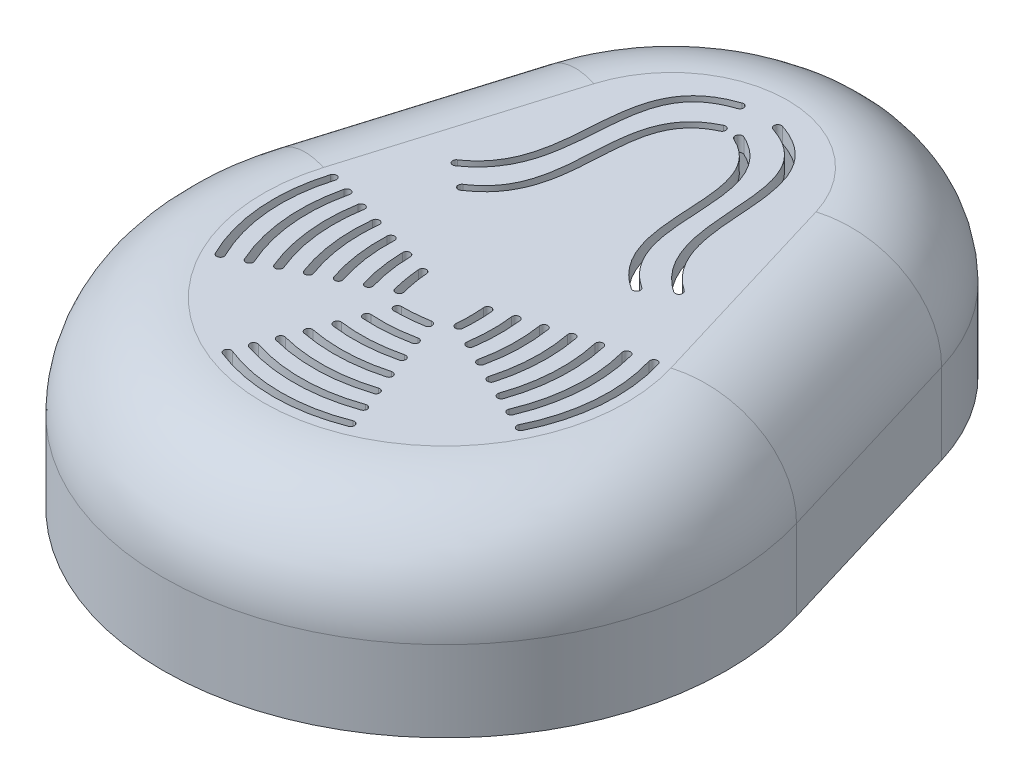
SolidWorks part; units mm, degrees
ref_plane "Alzado" through (0, 0, 0) normal (0, 0, 1) x (1, 0, 0)
ref_plane "Planta" through (0, 0, 0) normal (0, 1, 0) x (1, 0, 0)
ref_plane "Vista lateral" through (0, 0, 0) normal (1, 0, 0) x (0, 0, -1)
sketch "Croquis6" plane through (0, 0, 0) normal (0, 1, 0) x (1, 0, 0)
  line L0 (-53.6123, 2.1778) -> (-41.1666, 43.4222)
  line L1 (41.1666, 43.4222) -> (53.6123, 2.1778)
  arc A0 (41.1666, 43.4222) -> (-41.1666, 43.4222) centre (0, 31) ccw
  arc A1 (-53.6123, 2.1778) -> (53.6123, 2.1778) centre (0, -14) ccw
  dimension "D2" = 43
  dimension "D3" = 56
  dimension "D1" = 45
  dimension "D4" = 14
extrude "Saliente-Extruir3" add sketch "Croquis6" along normal blind 36
fillet "Redondeo1" radius 20 4 edges at (0, 36, -74) (-47.3895, 36, -22.8) (0, 36, 70) (47.3895, 36, -22.8)
shell "Vaciado1" thickness 3
sketch "Croquis8" plane through (0, 36, 0) normal (0, 1, 0) x (1, 0, 0)
  line L0 (-7.4874, -11.7407) -> (-32.5503, -4.1778) construction
  line L1 (-30.4675, -29.0909) -> (-6.5155, -17.4301) construction
  line L2 (-33.8818, -16.8327) -> (0, -14) construction
  line L3 (-7.4874, -11.7407) -> (-6.5155, -17.4301) construction
  line L4 (0, -14) -> (0, 54) construction
  line L5 (-22.5, 11) -> (-17.7432, 7.3431) construction
  line L6 (-32.0937, -23.6844) -> (-6.5898, -15.9885) construction
  line L7 (-16, 21) -> (-11.2432, 17.3431) construction
  line L8 (-53.6123, 2.1778) -> (-34.4651, -3.6) construction
  line L9 (53.6123, 2.1778) -> (34.4651, -3.6) construction
  line L10 (-2.8753, -21.2731) -> (-12.5, -45.6188) construction
  line L11 (12.5, -45.6188) -> (2.8753, -20.7786) construction
  line L12 (-2.8753, -21.2731) -> (2.8753, -20.7786) construction
  line L13 (7.0082, -17.4713) -> (30.4675, -29.0909) construction
  line L14 (32.5503, -4.1778) -> (6.9946, -11.6995) construction
  line L15 (7.0082, -17.4713) -> (6.9946, -11.6995) construction
  line L16 (-6.6429, -10.2169) -> (-30.1809, 1.2423) construction
  line L17 (36.2644, -6.0707) -> (11.4572, -15.7801) construction
  line L18 (11.9713, -21.529) -> (36.3497, -31.0705) construction
  line L19 (-8.2432, 37.3431) -> (-13, 41) construction
  line L20 (-4, 49) -> (-2, 43.3431) construction
  arc A0 (-32.5503, -4.1778) -> (-30.4675, -29.0909) centre (0, -14) ccw
  arc A1 (-34.4651, -3.6) -> (34.4651, -3.6) centre (0, -14) ccw construction
  arc A2 (-28.6933, -5.3417) -> (-26.5651, -27.1911) centre (4.3987, -13.1468) ccw
  arc A3 (-24.7127, -6.5428) -> (-22.6273, -25.274) centre (8.7974, -12.2936) ccw
  arc A4 (-20.6065, -7.7819) -> (-18.6538, -23.3395) centre (13.1961, -11.4405) ccw
  arc A5 (-16.3709, -9.06) -> (-14.6443, -21.3875) centre (17.5948, -10.5873) ccw
  arc A6 (-12.0004, -10.3788) -> (-10.5983, -19.4178) centre (21.9935, -9.7341) ccw
  arc A7 (-7.4874, -11.7407) -> (-6.5155, -17.4301) centre (26.3922, -8.8809) ccw
  arc A8 (-31.1143, -4.6111) -> (-29.1233, -28.4251) centre (0, -14) ccw
  arc A9 (-27.2333, -5.686) -> (-25.1991, -26.5715) centre (4.3987, -13.1468) ccw
  arc A10 (-23.2343, -6.7965) -> (-21.2409, -24.7013) centre (8.7974, -12.2936) ccw
  arc A11 (-19.1152, -7.9433) -> (-17.2486, -22.8145) centre (13.1961, -11.4405) ccw
  arc A12 (-14.8724, -9.1274) -> (-13.2219, -20.911) centre (17.5948, -10.5873) ccw
  arc A13 (-10.5007, -10.3504) -> (-9.1605, -18.9905) centre (21.9935, -9.7341) ccw
  arc A14 (-5.9927, -11.6145) -> (-5.0637, -17.0529) centre (26.3922, -8.8809) ccw
  arc A15 (-32.5503, -4.1778) -> (-31.1143, -4.6111) centre (-31.8323, -4.3944) cw
  arc A16 (-30.4675, -29.0909) -> (-29.1233, -28.4251) centre (-29.7954, -28.758) ccw
  arc A17 (-28.6933, -5.3417) -> (-27.2333, -5.686) centre (-27.9633, -5.5138) cw
  arc A18 (-26.5651, -27.1911) -> (-25.1991, -26.5715) centre (-25.8821, -26.8813) ccw
  arc A19 (-24.7127, -6.5428) -> (-23.2343, -6.7965) centre (-23.9735, -6.6697) cw
  arc A20 (-22.6273, -25.274) -> (-21.2409, -24.7013) centre (-21.9341, -24.9876) ccw
  arc A21 (-20.6065, -7.7819) -> (-19.1152, -7.9433) centre (-19.8609, -7.8626) cw
  arc A22 (-18.6538, -23.3395) -> (-17.2486, -22.8145) centre (-17.9512, -23.077) ccw
  arc A23 (-16.3709, -9.06) -> (-14.8724, -9.1274) centre (-15.6217, -9.0937) cw
  arc A24 (-14.6443, -21.3875) -> (-13.2219, -20.911) centre (-13.9331, -21.1492) ccw
  arc A25 (-12.0004, -10.3788) -> (-10.5007, -10.3504) centre (-11.2505, -10.3646) cw
  arc A26 (-10.5983, -19.4178) -> (-9.1605, -18.9905) centre (-9.8794, -19.2042) ccw
  arc A27 (-7.4874, -11.7407) -> (-5.9927, -11.6145) centre (-6.74, -11.6776) cw
  arc A28 (-6.5155, -17.4301) -> (-5.0637, -17.0529) centre (-5.7896, -17.2415) ccw
  arc A29 (-12.5, -45.6188) -> (12.5, -45.6188) centre (0, -14) ccw
  arc A30 (-11.0188, -41.8722) -> (10.9319, -41.5718) centre (-0.4837, -9.5455) ccw
  arc A31 (-9.4902, -38.0055) -> (9.3496, -37.4879) centre (-0.9675, -5.091) ccw
  arc A32 (-7.9133, -34.0168) -> (7.7529, -33.367) centre (-1.4512, -0.6365) ccw
  arc A33 (-6.2868, -29.9024) -> (6.1417, -29.2088) centre (-1.935, 3.8179) ccw
  arc A34 (-4.6084, -25.657) -> (4.5159, -25.0129) centre (-2.4187, 8.2724) ccw
  arc A35 (-2.8753, -21.2731) -> (2.8753, -20.7786) centre (-2.9024, 12.7269) ccw
  arc A36 (-11.9485, -44.2239) -> (11.9485, -44.2239) centre (0, -14) ccw
  arc A37 (-10.554, -40.446) -> (10.4283, -40.1589) centre (-0.4837, -9.5455) ccw
  arc A38 (-9.1142, -36.5534) -> (8.8944, -36.0586) centre (-0.9675, -5.091) ccw
  arc A39 (-7.6282, -32.5441) -> (7.3468, -31.923) centre (-1.4512, -0.6365) ccw
  arc A40 (-6.0948, -28.4147) -> (5.7854, -27.7518) centre (-1.935, 3.8179) ccw
  arc A41 (-4.5118, -24.1601) -> (4.21, -23.5444) centre (-2.4187, 8.2724) ccw
  arc A42 (-2.8765, -19.7731) -> (2.6204, -19.3004) centre (-2.9024, 12.7269) ccw
  arc A43 (-12.5, -45.6188) -> (-11.9485, -44.2239) centre (-12.2243, -44.9213) cw
  arc A44 (12.5, -45.6188) -> (11.9485, -44.2239) centre (12.2243, -44.9213) ccw
  arc A45 (-11.0188, -41.8722) -> (-10.554, -40.446) centre (-10.7864, -41.1591) cw
  arc A46 (10.9319, -41.5718) -> (10.4283, -40.1589) centre (10.6801, -40.8653) ccw
  arc A47 (-9.4902, -38.0055) -> (-9.1142, -36.5534) centre (-9.3022, -37.2795) cw
  arc A48 (9.3496, -37.4879) -> (8.8944, -36.0586) centre (9.122, -36.7733) ccw
  arc A49 (-7.9133, -34.0168) -> (-7.6282, -32.5441) centre (-7.7708, -33.2805) cw
  arc A50 (7.7529, -33.367) -> (7.3468, -31.923) centre (7.5498, -32.645) ccw
  arc A51 (-6.2868, -29.9024) -> (-6.0948, -28.4147) centre (-6.1908, -29.1586) cw
  arc A52 (6.1417, -29.2088) -> (5.7854, -27.7518) centre (5.9636, -28.4803) ccw
  arc A53 (-4.6084, -25.657) -> (-4.5118, -24.1601) centre (-4.5601, -24.9085) cw
  arc A54 (4.5159, -25.0129) -> (4.21, -23.5444) centre (4.363, -24.2786) ccw
  arc A55 (-2.8753, -21.2731) -> (-2.8765, -19.7731) centre (-2.8759, -20.5231) cw
  arc A56 (2.8753, -20.7786) -> (2.6204, -19.3004) centre (2.7478, -20.0395) ccw
  arc A57 (30.4675, -29.0909) -> (32.5503, -4.1778) centre (0, -14) ccw
  arc A58 (26.8572, -27.3027) -> (28.3867, -5.4032) centre (-4.4793, -14.1109) ccw
  arc A59 (23.1314, -25.4572) -> (24.1852, -6.6398) centre (-8.9586, -14.2219) ccw
  arc A60 (19.2879, -23.5535) -> (19.9456, -7.8876) centre (-13.4379, -14.3328) ccw
  arc A61 (15.3233, -21.5898) -> (15.6676, -9.1468) centre (-17.9172, -14.4437) ccw
  arc A62 (11.2325, -19.5636) -> (11.3508, -10.4173) centre (-22.3965, -14.5547) ccw
  arc A63 (7.0082, -17.4713) -> (6.9946, -11.6995) centre (-26.8758, -14.6656) ccw
  arc A64 (29.1233, -28.4251) -> (31.1143, -4.6111) centre (0, -14) ccw
  arc A65 (25.4747, -26.7207) -> (26.9368, -5.7874) centre (-4.4793, -14.1109) ccw
  arc A66 (21.7156, -24.9615) -> (22.723, -6.9743) centre (-8.9586, -14.2219) ccw
  arc A67 (17.8441, -23.1467) -> (18.4728, -8.172) centre (-13.4379, -14.3328) ccw
  arc A68 (13.8568, -21.2745) -> (14.186, -9.3804) centre (-17.9172, -14.4437) ccw
  arc A69 (9.7489, -19.3426) -> (9.862, -10.5998) centre (-22.3965, -14.5547) ccw
  arc A70 (5.5134, -17.3475) -> (5.5003, -11.8303) centre (-26.8758, -14.6656) ccw
  arc A71 (30.4675, -29.0909) -> (29.1233, -28.4251) centre (29.7954, -28.758) cw
  arc A72 (32.5503, -4.1778) -> (31.1143, -4.6111) centre (31.8323, -4.3944) ccw
  arc A73 (26.8572, -27.3027) -> (25.4747, -26.7207) centre (26.166, -27.0117) cw
  arc A74 (28.3867, -5.4032) -> (26.9368, -5.7874) centre (27.6617, -5.5953) ccw
  arc A75 (23.1314, -25.4572) -> (21.7156, -24.9615) centre (22.4235, -25.2094) cw
  arc A76 (24.1852, -6.6398) -> (22.723, -6.9743) centre (23.4541, -6.8071) ccw
  arc A77 (19.2879, -23.5535) -> (17.8441, -23.1467) centre (18.566, -23.3501) cw
  arc A78 (19.9456, -7.8876) -> (18.4728, -8.172) centre (19.2092, -8.0298) ccw
  arc A79 (15.3233, -21.5898) -> (13.8568, -21.2745) centre (14.5901, -21.4322) cw
  arc A80 (15.6676, -9.1468) -> (14.186, -9.3804) centre (14.9268, -9.2636) ccw
  arc A81 (11.2325, -19.5636) -> (9.7489, -19.3426) centre (10.4907, -19.4531) cw
  arc A82 (11.3508, -10.4173) -> (9.862, -10.5998) centre (10.6064, -10.5086) ccw
  arc A83 (7.0082, -17.4713) -> (5.5134, -17.3475) centre (6.2608, -17.4094) cw
  arc A84 (6.9946, -11.6995) -> (5.5003, -11.8303) centre (6.2474, -11.7649) ccw
  arc A85 (22.0193, 37.6444) -> (-22.0193, 37.6444) centre (0, 31) ccw construction
  arc A86 (-4, 49) -> (-3.5263, 47.5768) centre (-3.7631, 48.2884) cw
  arc A87 (-22.5, 11) -> (-21.655, 9.7606) centre (-22.0775, 10.3803) ccw
  arc A88 (-2, 43.3431) -> (-1.3615, 41.9858) centre (-1.6807, 42.6645) cw
  arc A89 (-17.7432, 7.3431) -> (-16.9293, 6.0832) centre (-17.3362, 6.7132) ccw
  arc A90 (4, 49) -> (3.5263, 47.5768) centre (3.7631, 48.2884) ccw
  arc A91 (22.5, 11) -> (21.655, 9.7606) centre (22.0775, 10.3803) cw
  arc A92 (2, 43.3431) -> (1.3615, 41.9858) centre (1.6807, 42.6645) ccw
  arc A93 (17.7432, 7.3431) -> (16.9293, 6.0832) centre (17.3362, 6.7132) cw
  spline S0 degree 3 poles (-4, 49) (-22.3057, 42.9068) (-8.3543, 20.6444) (-22.5, 11) knots 0 0 0 0 1 1 1 1
  spline S1 degree 3 poles (-2, 43.3431) (-16.8249, 36.3689) (-4.2167, 16.0809) (-17.7432, 7.3431) knots 0 0 0 0 1 1 1 1
  spline S2 degree 3 poles (4, 49) (22.3057, 42.9068) (8.3543, 20.6444) (22.5, 11) knots 0 0 0 0 1 1 1 1
  spline S3 degree 3 poles (2, 43.3431) (16.8249, 36.3689) (4.2167, 16.0809) (17.7432, 7.3431) knots 0 0 0 0 1 1 1 1
  spline S4 degree 1 poles (-3.5263, 47.5768) (-21.655, 9.7606) knots 0 0 1 1 construction
  spline S5 degree 3 poles (-3.5263, 47.5768) (-3.7864, 47.4902) (-4.3118, 47.3031) (-5.2759, 46.9108) (-6.3734, 46.3724) (-7.5179, 45.6615) (-8.842, 44.6317) (-10.1604, 43.1989) (-11.3276, 41.2396) (-12.1619, 39.0334) (-12.9152, 35.7913) (-13.3453, 31.2785) (-13.6752, 25.5051) (-14.3981, 20.6711) (-15.6553, 16.9525) (-17.0463, 14.2974) (-18.6669, 12.2566) (-20.2605, 10.7791) (-21.1848, 10.0812) (-21.655, 9.7606) knots 0 0 0 0 0.015625 0.03125 0.0625 0.09375 0.125 0.1875 0.25 0.3125 0.375 0.5 0.625 0.75 0.8125 0.875 0.9375 0.96875 1 1 1 1
  spline S6 degree 1 poles (-1.3615, 41.9858) (-16.9293, 6.0832) knots 0 0 1 1 construction
  spline S7 degree 3 poles (-1.3615, 41.9858) (-1.766, 41.7955) (-2.5811, 41.3654) (-3.9442, 40.4606) (-5.3288, 39.1895) (-6.556, 37.465) (-7.4507, 35.521) (-8.0696, 33.3632) (-8.6022, 30.2377) (-8.8703, 25.9645) (-9.1351, 20.576) (-9.8541, 16.0966) (-11.1027, 12.6635) (-12.4731, 10.2215) (-14.0519, 8.3546) (-15.5905, 7.0087) (-16.4788, 6.3741) (-16.9293, 6.0832) knots 0 0 0 0 0.03125 0.0625 0.125 0.1875 0.25 0.3125 0.375 0.5 0.625 0.75 0.8125 0.875 0.9375 0.96875 1 1 1 1
  spline S8 degree 1 poles (3.5263, 47.5768) (21.655, 9.7606) knots 0 0 1 1 construction
  spline S9 degree 3 poles (3.5263, 47.5768) (3.7864, 47.4902) (4.3118, 47.3031) (5.2759, 46.9108) (6.3734, 46.3724) (7.5179, 45.6615) (8.842, 44.6317) (10.1604, 43.1989) (11.3276, 41.2396) (12.1619, 39.0334) (12.9152, 35.7913) (13.3453, 31.2785) (13.6752, 25.5051) (14.3981, 20.6711) (15.6553, 16.9525) (17.0463, 14.2974) (18.6669, 12.2566) (20.2605, 10.7791) (21.1848, 10.0812) (21.655, 9.7606) knots 0 0 0 0 0.015625 0.03125 0.0625 0.09375 0.125 0.1875 0.25 0.3125 0.375 0.5 0.625 0.75 0.8125 0.875 0.9375 0.96875 1 1 1 1
  spline S10 degree 1 poles (1.3615, 41.9858) (16.9293, 6.0832) knots 0 0 1 1 construction
  spline S11 degree 3 poles (1.3615, 41.9858) (1.766, 41.7955) (2.5811, 41.3654) (3.9442, 40.4606) (5.3288, 39.1895) (6.556, 37.465) (7.4507, 35.521) (8.0696, 33.3632) (8.6022, 30.2377) (8.8703, 25.9645) (9.1351, 20.576) (9.8541, 16.0966) (11.1027, 12.6635) (12.4731, 10.2215) (14.0519, 8.3546) (15.5905, 7.0087) (16.4788, 6.3741) (16.9293, 6.0832) knots 0 0 0 0 0.03125 0.0625 0.125 0.1875 0.25 0.3125 0.375 0.5 0.625 0.75 0.8125 0.875 0.9375 0.96875 1 1 1 1
  point P11 (-7.0014, -14.5854)
  point P40 (2.4378, -16.2454)
  point P186 (0, -14)
  dimension "D1" = 2
  dimension "D6" = 1.5
  dimension "D4" = 25
  dimension "D5" = 7
  dimension "D8" = 8
  dimension "D9" = 26
  dimension "D10" = 32
  dimension "D11" = 45
  dimension "D12" = 6
  dimension "D13" = 8
  dimension "D14" = 20
  dimension "D15" = 10
  dimension "D16" = 5
  dimension "D17" = 10
  dimension "D18" = 20
  dimension "D19" = 6
  dimension "D20" = 4
  dimension "D21" = 1.5
  dimension "D22" = 1.5
  dimension "D2" = 7
  dimension "D3" = 3
  dimension "D7" = 3
extrude "Cortar-Extruir2" cut sketch "Croquis8" against normal through all
sketch "Croquis10" plane through (0, 0, 0) normal (0, -1, 0) x (1, 0, 0)
  line L23 (40.1844, 35) -> (48.6621, 35)
  line L24 (42.9884, 45) -> (40.1844, 45)
  line L25 (40.1844, 35) -> (48.6621, 35)
  line L26 (42.9884, 45) -> (40.1844, 45)
  line L27 (-48.6621, 35) -> (-40.1844, 35)
  line L28 (-38.7941, -40.9) -> (-34.3029, -40.9)
  line L29 (-41.8116, -30.9) -> (-38.7941, -40.9)
  line L30 (-34.3029, -30.9) -> (-41.8116, -30.9)
  line L31 (-38.7941, -40.9) -> (-34.3029, -40.9)
  line L32 (-41.8116, -30.9) -> (-38.7941, -40.9)
  line L33 (-34.3029, -30.9) -> (-41.8116, -30.9)
  line L34 (-40.1844, 45) -> (-42.9884, 45)
  line L35 (-48.6621, 35) -> (-40.1844, 35)
  line L36 (-40.1844, 45) -> (-42.9884, 45)
  line L38 (38.7941, -40.9) -> (41.8116, -30.9)
  line L39 (41.8116, -30.9) -> (34.3029, -30.9)
  line L40 (34.3029, -40.9) -> (38.7941, -40.9)
  line L41 (38.7941, -40.9) -> (41.8116, -30.9)
  line L42 (41.8116, -30.9) -> (34.3029, -30.9)
  line L43 (34.3029, -40.9) -> (38.7941, -40.9)
  arc A19 (-34.3029, -40.9) -> (-34.3029, -30.9) centre (-34.3029, -35.9) ccw
  arc A20 (48.6621, 35) -> (42.9884, 45) centre (0, 14) ccw
  arc A21 (40.1844, 45) -> (40.1844, 35) centre (40.1844, 40) ccw
  arc A22 (48.6621, 35) -> (42.9884, 45) centre (0, 14) ccw
  arc A23 (40.1844, 45) -> (40.1844, 35) centre (40.1844, 40) ccw
  arc A24 (-34.3029, -40.9) -> (-34.3029, -30.9) centre (-34.3029, -35.9) ccw
  arc A25 (34.3029, -30.9) -> (34.3029, -40.9) centre (34.3029, -35.9) ccw
  arc A26 (-42.9884, 45) -> (-48.6621, 35) centre (0, 14) ccw
  arc A27 (-40.1844, 35) -> (-40.1844, 45) centre (-40.1844, 40) ccw
  arc A28 (-42.9884, 45) -> (-48.6621, 35) centre (0, 14) ccw
  arc A29 (-40.1844, 35) -> (-40.1844, 45) centre (-40.1844, 40) ccw
  arc A30 (34.3029, -30.9) -> (34.3029, -40.9) centre (34.3029, -35.9) ccw
  dimension "D1" = 0
  dimension "D2" = 0
  dimension "D3" = 0
  dimension "D4" = 0
extrude "Saliente-Extruir4" add sketch "Croquis10" against normal up to next
sketch "Croquis11" plane through (0, 0, 0) normal (0, -1, 0) x (1, 0, 0)
  circle A1 centre (34.3029, -35.9) radius 3.6 construction
  circle A5 centre (-34.3029, -35.9) radius 3.6 construction
  circle A6 centre (34.3029, -35.9) radius 3.6
  circle A7 centre (-34.3029, -35.9) radius 3.6
  circle A8 centre (-40.1844, 40) radius 3.6 construction
  circle A9 centre (40.1844, 40) radius 3.6 construction
  circle A10 centre (-40.1844, 40) radius 3.6
  circle A11 centre (40.1844, 40) radius 3.6
extrude "Cortar-Extruir3" cut sketch "Croquis11" against normal blind 3 separate body
equation "\"dim\"= 6"
